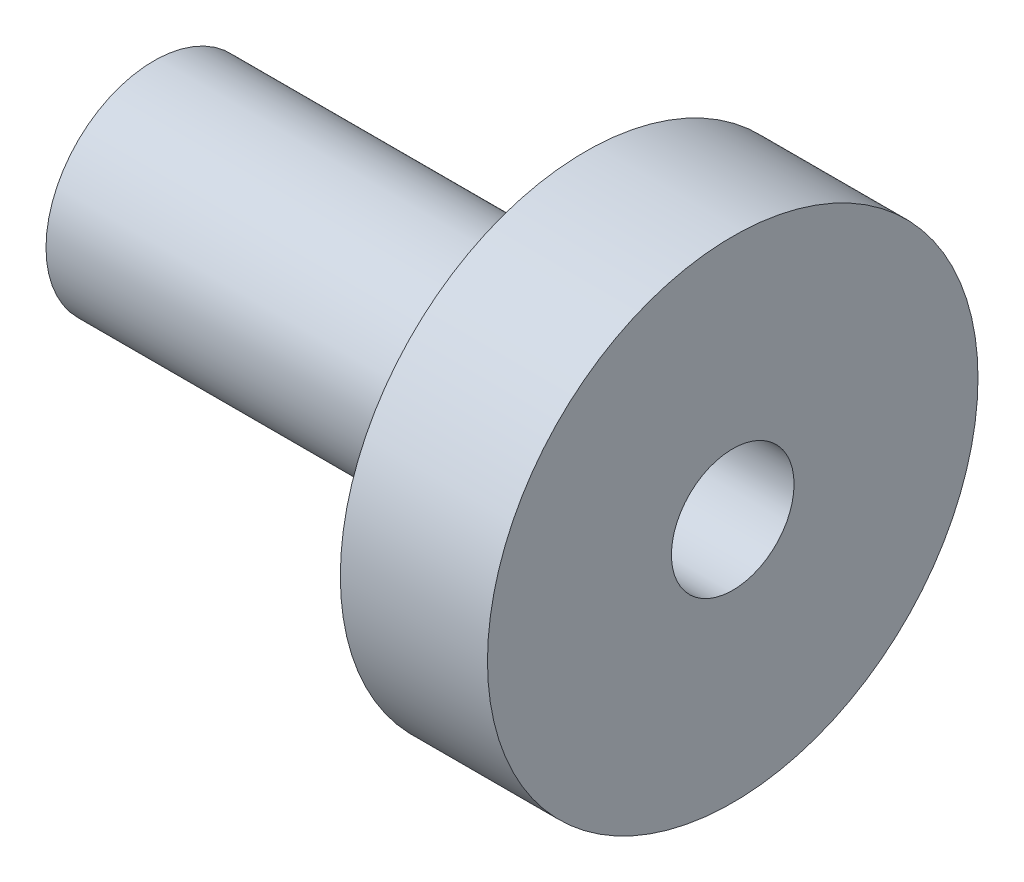
SolidWorks part; units mm, degrees
ref_plane "Front Plane" through (0, 0, 0) normal (0, 0, 1) x (1, 0, 0)
ref_plane "Top Plane" through (0, 0, 0) normal (0, 1, 0) x (1, 0, 0)
ref_plane "Right Plane" through (0, 0, 0) normal (1, 0, 0) x (0, 0, -1)
sketch "Sketch1" plane through (0, 0, 0) normal (0, 0, 1) x (1, 0, 0)
  line L0 (-1364.9787, 0) -> (66883.9584, 0) construction
  line L1 (0, 0) -> (0, 6.35)
  line L2 (0, 6.35) -> (-3.81, 6.35)
  line L3 (-3.81, 6.35) -> (-3.81, 2.794)
  line L4 (-3.81, 2.794) -> (-14.986, 2.794)
  line L5 (-14.986, 2.794) -> (-14.986, 0)
  line L6 (-14.986, 0) -> (0, 0)
  dimension "D1" = 3.81
  dimension "D2" = 14.986
  dimension "D3" = 12.7
  dimension "D4" = 2.794
revolve "Revolve2" add sketch "Sketch1" angle 360 about L0
sketch "Sketch4" plane through (0, 0, 0) normal (0, 0, 1) x (1, 0, 0)
  line L0 (0, 0) -> (-14.986, 0) construction
  line L1 (-14.986, 2.794) -> (-14.986, -2.794) construction
  line L2 (0, 0) -> (0, 1.5875)
  line L3 (0, -6.35) -> (0, 6.35) construction
  line L4 (0, 1.5875) -> (-2.54, 1.5875)
  line L5 (-2.54, 1.5875) -> (-3.4939, 0)
  line L6 (-3.4939, 0) -> (0, 0)
  dimension "D1" = 3.175
  dimension "D2" = 59
  dimension "D3" = 2.54
revolve "Cut-Revolve1" cut sketch "Sketch4" angle 360 about L0
sketch "Sketch5" plane through (0, 0, 0) normal (0, 0, 1) x (1, 0, 0)
  line L0 (-1008.3786, 4.8088) -> (48991.6214, 4.8088) construction
  line L1 (0, -6.35) -> (0, 6.35) construction
  line L3 (-0.6779, 4.8088) -> (0.6779, 4.8088)
  arc A0 (0.6779, 4.8088) -> (-0.6779, 4.8088) centre (0, 4.8088) ccw
  dimension "D1" = 1.3559
